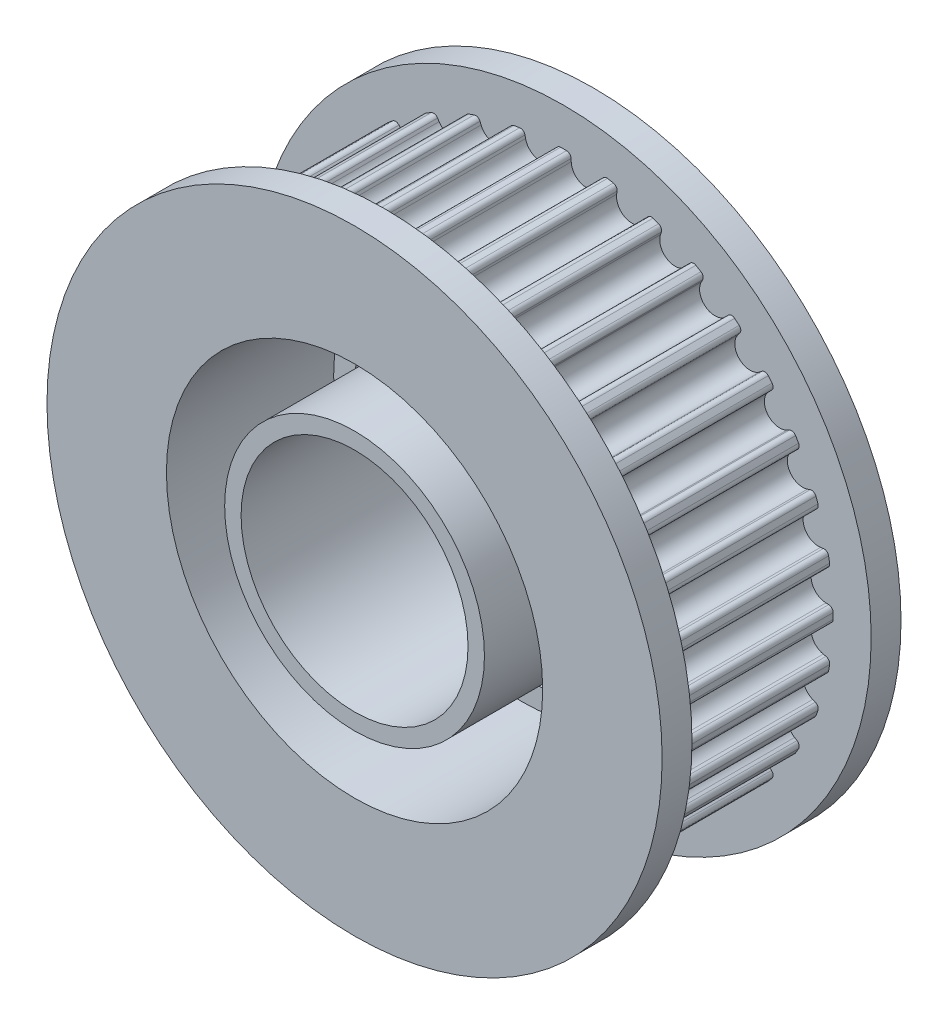
SolidWorks part; units mm, degrees
ref_plane "前视基准面" through (0, 0, 0) normal (0, 0, 1) x (1, 0, 0)
ref_plane "上视基准面" through (0, 0, 0) normal (0, 1, 0) x (1, 0, 0)
ref_plane "右视基准面" through (0, 0, 0) normal (1, 0, 0) x (0, 0, -1)
sketch "Sketch2" plane through (0, 0, 0) normal (0, 0, 1) x (1, 0, 0)
  circle A0 centre (0, 0) radius 45.15
  dimension "D1" = 90.3
extrude "Extrude1" add sketch "Sketch2" along normal mid plane 30
sketch "Sketch1" plane through (0, 0, 15) normal (0, 0, 1) x (1, 0, 0)
  line L0 (0, 0) -> (0, 45.835) construction
  line L1 (0, 0) -> (-3.9948, 45.6606) construction
  line L2 (-1.2656, 44.3946) -> (-1.2821, 43.9222)
  line L3 (-6.4627, 43.9399) -> (-6.3644, 43.4775)
  circle A0 centre (0, 0) radius 45.835 construction
  arc A1 (-0.4946, 45.1473) -> (-7.3526, 44.5473) centre (0, 0) ccw
  arc A2 (-6.3644, 43.4775) -> (-1.2821, 43.9222) centre (-3.8505, 44.0119) ccw
  arc A3 (-0.4946, 45.1473) -> (-1.2656, 44.3946) centre (-0.4861, 44.3673) ccw
  arc A4 (-7.3526, 44.5473) -> (-6.4627, 43.9399) centre (-7.2256, 43.7777) cw
  point P4 (45.6606, 3.9948)
  point P5 (44.2732, 11.863)
  point P6 (41.5406, 19.3707)
  point P7 (37.5458, 26.2899)
  point P8 (32.4102, 32.4102)
  point P9 (26.2899, 37.5458)
  point P10 (19.3707, 41.5406)
  point P11 (11.863, 44.2732)
  point P12 (3.9948, 45.6606)
  point P13 (-3.9948, 45.6606)
  point P14 (-11.863, 44.2732)
  point P15 (-19.3707, 41.5406)
  point P16 (-26.2899, 37.5458)
  point P17 (-32.4102, 32.4102)
  point P18 (-37.5458, 26.2899)
  point P19 (-41.5406, 19.3707)
  point P20 (-44.2732, 11.863)
  point P21 (-45.6606, 3.9948)
  point P22 (-45.6606, -3.9948)
  point P23 (-44.2732, -11.863)
  point P24 (-41.5406, -19.3707)
  point P25 (-37.5458, -26.2899)
  point P26 (-32.4102, -32.4102)
  point P27 (-26.2899, -37.5458)
  point P28 (-19.3707, -41.5406)
  point P29 (-11.863, -44.2732)
  point P30 (-3.9948, -45.6606)
  point P31 (3.9948, -45.6606)
  point P32 (11.863, -44.2732)
  point P33 (19.3707, -41.5406)
  point P34 (26.2899, -37.5458)
  point P35 (32.4102, -32.4102)
  point P36 (37.5458, -26.2899)
  point P37 (41.5406, -19.3707)
  point P38 (44.2732, -11.863)
  point P39 (45.6606, -3.9948)
  dimension "D1" = 91.67
  dimension "D2" = 90.3
  dimension "D3" = 5.14
  dimension "D4" = 3.54
  dimension "D5" = 1.56
  dimension "D6" = 7
extrude "Extrude2" cut sketch "Sketch1" against normal through all
pattern_circular "CirPattern1" count 36 over 360 about axis through (0, 0, 0) along (0, 0, 1) of "Extrude2"
sketch "Sketch3" plane through (0, 0, -15) normal (0, 0, -1) x (-1, 0, 0)
  circle A0 centre (0, 0) radius 51.5
  dimension "D1" = 103
extrude "Extrude3" add sketch "Sketch3" along normal blind 5
sketch "Sketch4" plane through (0, 0, 15) normal (0, 0, 1) x (1, 0, 0)
  circle A0 centre (0, 0) radius 51.5
  circle A1 centre (0, 0) radius 51.5 construction
extrude "Extrude4" add sketch "Sketch4" along normal blind 5
sketch "Sketch6" plane through (0, 0, 0) normal (0, 1, 0) x (1, 0, 0)
  line L0 (0, 20) -> (0, -20) construction
  line L1 (51.5, 20) -> (-51.5, 20) construction
  line L2 (-51.5, -20) -> (51.5, -20) construction
  line L3 (0, 20) -> (19, 20)
  line L4 (19, 20) -> (19, -20)
  line L5 (19, -20) -> (0, -20)
  line L6 (21.75, -20) -> (31.5, -20)
  line L7 (31.5, -20) -> (31.5, 8)
  line L9 (21.75, 10) -> (21.75, -20)
  line L11 (31.5, 8) -> (28, 8)
  line L12 (28, 8) -> (28, 10)
  line L13 (28, 10) -> (21.75, 10)
  line L14 (0, 20) -> (0, -20)
  dimension "D1" = 63
  dimension "D2" = 43.5
  dimension "D3" = 28
  dimension "D4" = 38
  dimension "D5" = 56
  dimension "D6" = 2
revolve "Cut-Revolve1" cut sketch "Sketch6" angle 360 about L0
